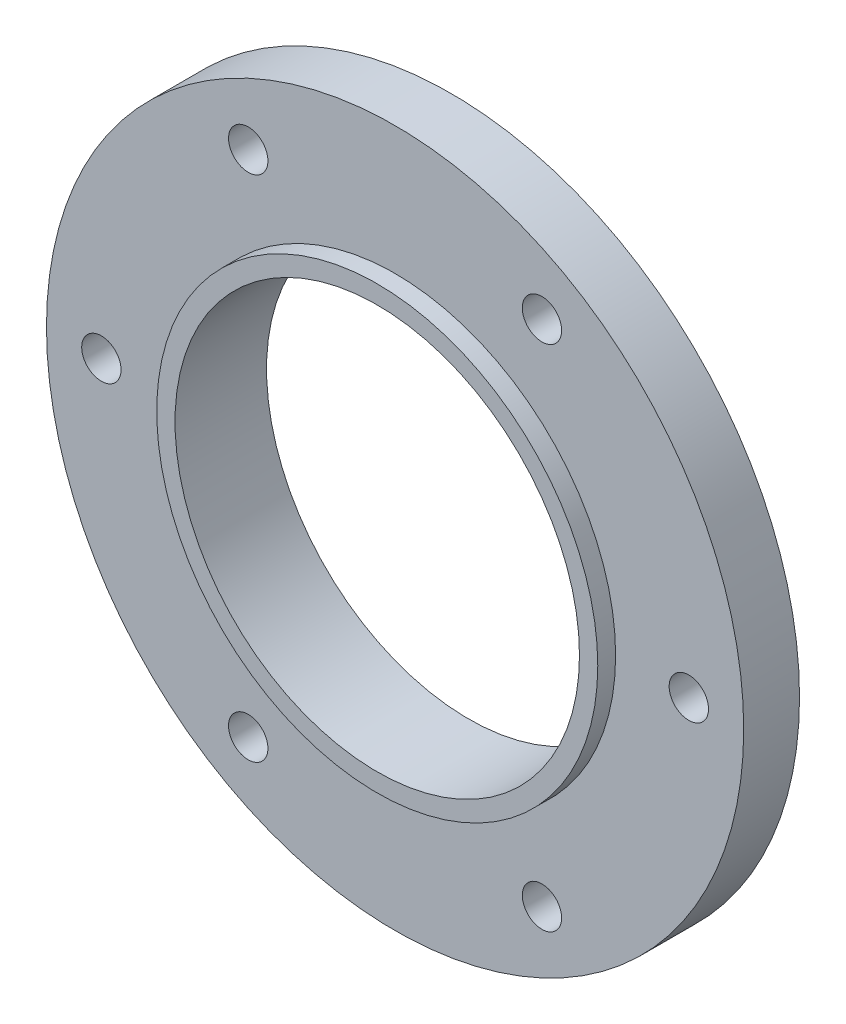
SolidWorks part; units mm, degrees
ref_plane "前视基准面" through (0, 0, 0) normal (0, 0, 1) x (1, 0, 0)
ref_plane "上视基准面" through (0, 0, 0) normal (0, 1, 0) x (1, 0, 0)
ref_plane "右视基准面" through (0, 0, 0) normal (1, 0, 0) x (0, 0, -1)
other "Configuration Table"
sketch "草图1" plane through (0, 0, 0) normal (0, 1, 0) x (1, 0, 0)
  line L0 (0, 0) -> (0, 14.9955) construction
  line L2 (24.1, 0) -> (38.1, 0)
  line L4 (24.1, 6.1) -> (38.1, 6.1)
  line L5 (38.1, 0) -> (38.1, 6.1)
  line L6 (22.1, 8.05) -> (24.1, 8.05)
  line L7 (24.1, 8.05) -> (24.1, 6.1)
  line L9 (22.1, -1.95) -> (24.1, -1.95)
  line L10 (24.1, -1.95) -> (24.1, 0)
  line L11 (22.1, 8.05) -> (22.1, -1.95)
  line L12 (22.1, 3.05) -> (29.5052, 3.05) construction
  dimension "D1" = 6.1
  dimension "D2" = 38.1
  dimension "D3" = 14
  dimension "D4" = 2
  dimension "D5" = 10
revolve "旋转1" add sketch "草图1" angle 360 about L0
sketch "草图3" plane through (0, 0, -6.1) normal (0, 0, -1) x (-1, 0, 0)
  line L0 (0, 0) -> (-32.1, 0) construction
  circle A0 centre (0, 0) radius 32.1 construction
  circle A1 centre (-32.1, 0) radius 2.15
  circle A2 centre (-16.05, 27.7994) radius 2.15
  circle A3 centre (16.05, 27.7994) radius 2.15
  circle A4 centre (32.1, 0) radius 2.15
  circle A5 centre (16.05, -27.7994) radius 2.15
  circle A6 centre (-16.05, -27.7994) radius 2.15
  dimension "D1" = 64.2
  dimension "D2" = 4.3
  dimension "D3" = 6
extrude "切除-拉伸2" cut sketch "草图3" against normal blind 10
